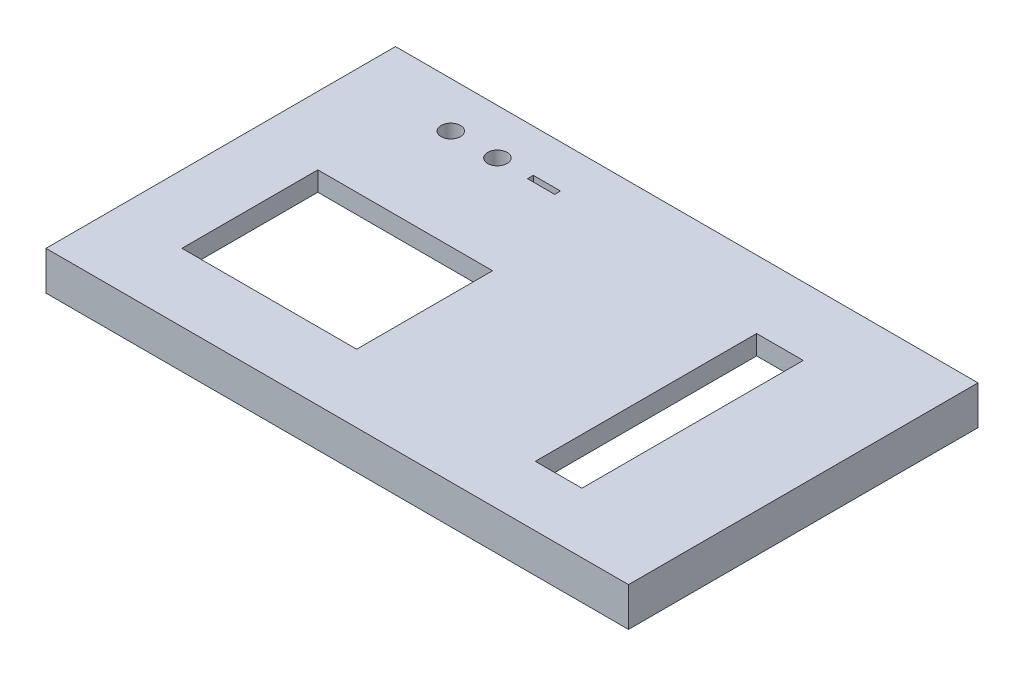
SolidWorks part; units mm, degrees
ref_plane "Front Plane" through (0, 0, 0) normal (0, 0, 1) x (1, 0, 0)
ref_plane "Top Plane" through (0, 0, 0) normal (0, 1, 0) x (1, 0, 0)
ref_plane "Right Plane" through (0, 0, 0) normal (1, 0, 0) x (0, 0, -1)
ref_plane "Plane1" through (0, 0, 0) normal (0, 1, 0) x (1, 0, 0)
sketch "Sketch1" plane through (0, 0, 0) normal (0, 1, 0) x (1, 0, 0)
  line L1 (-364.6808, 38.8525) -> (-219.6808, 38.8525)
  line L2 (-364.6808, 38.8525) -> (-364.6808, -46.1475)
  line L3 (-364.6808, -46.1475) -> (-219.6808, -46.1475)
  line L4 (-219.6808, 38.8525) -> (-219.6808, -46.1475)
  line L5 (-364.6808, 38.8525) -> (-219.6808, -46.1475) construction
  line L6 (-364.6808, -46.1475) -> (-219.6808, 38.8525) construction
  point P0 (-292.1808, -3.6475)
  dimension "D1" = 145
  dimension "D2" = 85
sketch "Sketch2" plane through (0, 0, 0) normal (0, 1, 0) x (1, 0, 0)
  line L1 (-349.6808, 3.8525) -> (-304.6808, 3.8525)
  line L2 (-349.6808, 3.8525) -> (-349.6808, -31.1475)
  line L3 (-349.6808, -31.1475) -> (-304.6808, -31.1475)
  line L4 (-304.6808, 3.8525) -> (-304.6808, -31.1475)
  dimension "D1" = 45
  dimension "D2" = 35
sketch "Sketch3" plane through (0, 0, 0) normal (0, 1, 0) x (1, 0, 0)
  line L1 (-256.6808, 23.8525) -> (-244.6808, 23.8525)
  line L2 (-256.6808, 23.8525) -> (-256.6808, -33.1475)
  line L3 (-256.6808, -33.1475) -> (-244.6808, -33.1475)
  line L4 (-244.6808, 23.8525) -> (-244.6808, -33.1475)
  dimension "D1" = 12
  dimension "D2" = 57
sketch "Sketch4" plane through (0, 0, 0) normal (0, 1, 0) x (1, 0, 0)
  circle A0 centre (-341.2138, 29.6273) radius 2.5
  circle A1 centre (-329.2138, 29.6273) radius 2.5
  dimension "D1" = 5
  dimension "D2" = 12
sketch "Sketch5" plane through (0, 0, 0) normal (0, 1, 0) x (1, 0, 0)
  line L5 (-320.7138, 28.8773) -> (-313.7138, 28.8773)
  line L6 (-320.7138, 28.8773) -> (-320.7138, 30.3773)
  line L7 (-320.7138, 30.3773) -> (-313.7138, 30.3773)
  line L8 (-313.7138, 28.8773) -> (-313.7138, 30.3773)
  line L9 (-320.7138, 28.8773) -> (-313.7138, 30.3773) construction
  line L10 (-320.7138, 30.3773) -> (-313.7138, 28.8773) construction
  point P0 (-317.2138, 29.6273)
  dimension "D1" = 7
  dimension "D2" = 1.5
ref_plane "Plane2" through (0, 0, 0) normal (0, 1, 0) x (1, 0, 0)
sketch "Sketch6" plane through (0, 0, 0) normal (0, 1, 0) x (1, 0, 0)
  line L0 (-364.6808, 38.8525) -> (-364.6808, -46.1475) construction
  line L1 (-367.1808, -48.6475) -> (-217.1808, -48.6475)
  line L2 (-367.1808, -48.6475) -> (-367.1808, 41.3525)
  line L3 (-367.1808, 41.3525) -> (-217.1808, 41.3525)
  line L4 (-217.1808, -48.6475) -> (-217.1808, 41.3525)
  line L5 (-367.1808, -48.6475) -> (-217.1808, 41.3525) construction
  line L6 (-367.1808, 41.3525) -> (-217.1808, -48.6475) construction
  line L7 (-219.6808, 38.8525) -> (-219.6808, -46.1475) construction
  point P0 (-292.1808, -3.6475)
  dimension "D1" = 150
  dimension "D2" = 90
extrude "Boss-Extrude1" add sketch "Sketch6" against normal blind 10
ref_plane "Plane3" through (0, -5, 0) normal (0, 1, 0) x (1, 0, 0)
sketch "Sketch7" plane through (0, -5, 0) normal (0, 1, 0) x (1, 0, 0)
  line L1 (-364.6808, 38.8525) -> (-219.6808, 38.8525)
  line L2 (-364.6808, 38.8525) -> (-364.6808, -46.1475)
  line L3 (-364.6808, -46.1475) -> (-219.6808, -46.1475)
  line L4 (-219.6808, 38.8525) -> (-219.6808, -46.1475)
  line L5 (-364.6808, 38.8525) -> (-219.6808, -46.1475) construction
  line L6 (-364.6808, -46.1475) -> (-219.6808, 38.8525) construction
  point P0 (-292.1808, -3.6475)
  dimension "D1" = 145
  dimension "D2" = 85
extrude "Cut-Extrude1" cut sketch "Sketch7" against normal blind 10
extrude "Cut-Extrude2" cut sketch "Sketch2" against normal blind 10
extrude "Cut-Extrude3" cut sketch "Sketch4" against normal blind 10
extrude "Cut-Extrude4" cut sketch "Sketch5" against normal blind 10
extrude "Cut-Extrude5" cut sketch "Sketch3" against normal blind 10
